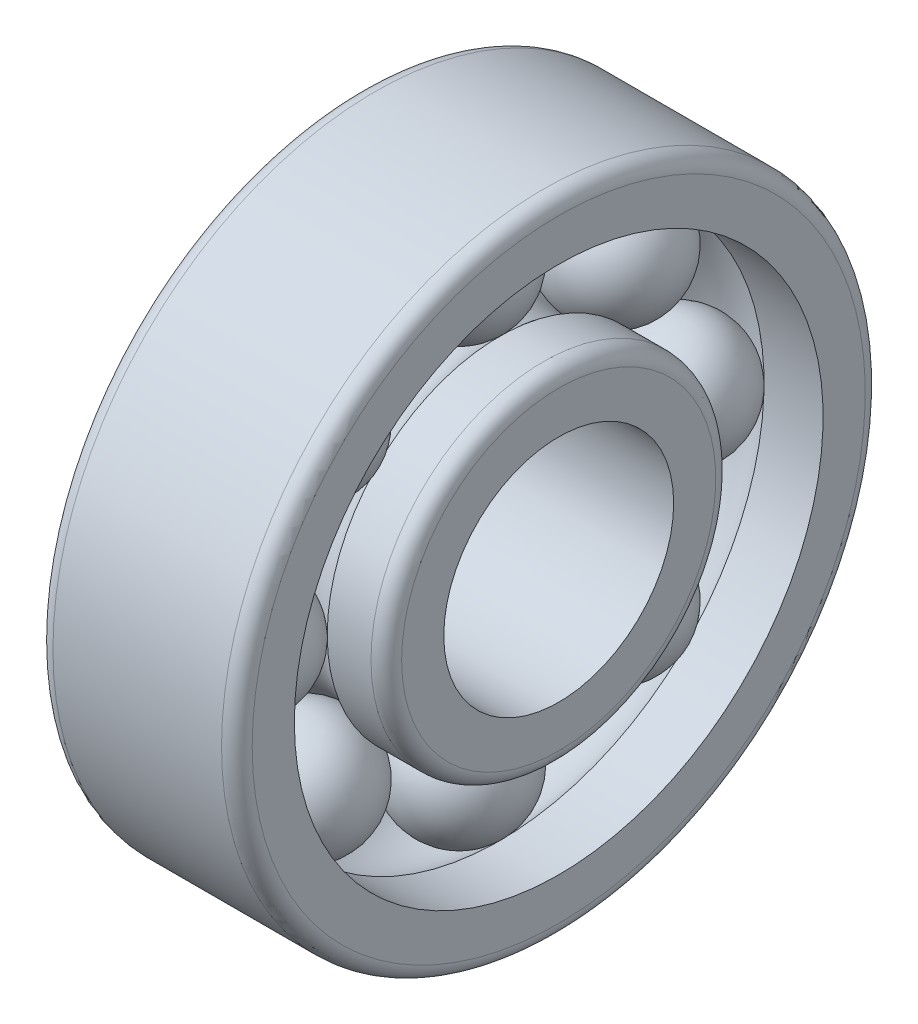
SolidWorks part; units mm, degrees
ref_plane "前视基准面" through (0, 0, 0) normal (0, 0, 1) x (1, 0, 0)
ref_plane "上视基准面" through (0, 0, 0) normal (0, 1, 0) x (1, 0, 0)
ref_plane "右视基准面" through (0, 0, 0) normal (1, 0, 0) x (0, 0, -1)
other "Configuration Table"
sketch "Sketch1" plane through (0, 0, 0) normal (0, 0, 1) x (1, 0, 0)
  line L0 (0, 0) -> (0, 14.25) construction
  line L1 (0, 0) -> (13.3688, 0) construction
  line L6 (-6.5, 7.5) -> (6.5, 7.5)
  line L7 (-6.5, 7.5) -> (-6.5, 21)
  line L8 (-6.5, 21) -> (6.5, 21)
  line L9 (6.5, 7.5) -> (6.5, 21)
  line L10 (-6.5, 7.5) -> (6.5, 21) construction
  line L11 (-6.5, 21) -> (6.5, 7.5) construction
  line L12 (0, 14.25) -> (-6.5, 14.25) construction
  line L14 (-6.5, 11.25) -> (6.5, 11.25)
  line L15 (-6.5, 11.25) -> (-6.5, 17.25)
  line L16 (-6.5, 17.25) -> (6.5, 17.25)
  line L17 (6.5, 11.25) -> (6.5, 17.25)
  line L18 (-6.5, 11.25) -> (6.5, 17.25) construction
  line L19 (-6.5, 17.25) -> (6.5, 11.25) construction
  circle A1 centre (0, 14.25) radius 4
  dimension "D1" = 13
  dimension "D4" = 8
  dimension "D2" = 21
  dimension "D3" = 7.5
  dimension "D5" = 6
revolve "Revolve1" add sketch "Sketch1" angle 360 about L1
sketch "Sketch3" plane through (0, 0, 0) normal (1, 0, 0) x (0, 0, -1)
  line L0 (0, 0) -> (0, 17.25) construction
  line L1 (0, 17.25) -> (0, 11.25) construction
  line L2 (0, 11.25) -> (0, 14.25) construction
  line L3 (0, 18.25) -> (0, 10.25) construction
  line L4 (0, 18.25) -> (0, 10.25)
  circle A0 centre (0, 0) radius 17.25 construction
  circle A1 centre (0, 0) radius 11.25 construction
  arc A2 (0, 10.25) -> (0, 18.25) centre (0, 14.25) ccw
  dimension "D1" = 8
revolve "Revolve2" add sketch "Sketch3" angle 360 about L4
pattern_circular "CirPattern2" count 8 over 360 about axis through (0, 0, 0) along (1, 0, 0) of bodies 108
fillet "Fillet1" radius 1 2 edges at (-6.5, 0, 21) (6.5, 0, 21)
fillet "Fillet3" radius 1 2 edges at (-6.5, 0, 11.25) (6.5, 0, 11.25)
